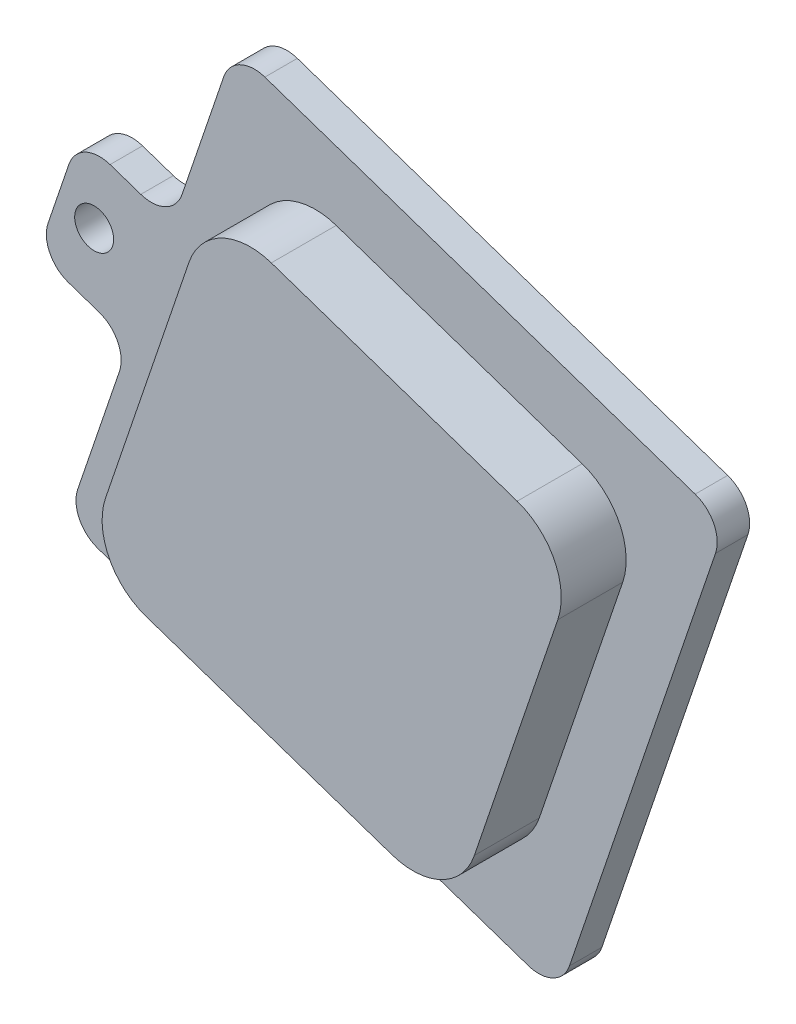
SolidWorks part; units mm, degrees
ref_plane "Front Plane" through (0, 0, 0) normal (0, 0, 1) x (1, 0, 0)
ref_plane "Top Plane" through (0, 0, 0) normal (0, 1, 0) x (1, 0, 0)
ref_plane "Right Plane" through (0, 0, 0) normal (1, 0, 0) x (0, 0, -1)
ref_plane "Plane1" through (0, 0, 3.175) normal (0, 0, 1) x (1, 0, 0)
sketch "Sketch1" plane through (0, 0, 3.175) normal (0, 0, 1) x (1, 0, 0)
  line L0 (54.9736, 15.2794) -> (-2.1524, 34.663)
  line L1 (-2.1524, 34.663) -> (-18.4755, -13.4431)
  line L2 (-18.4755, -13.4431) -> (38.6505, -32.8267)
  line L3 (38.6505, -32.8267) -> (54.9736, 15.2794)
extrude "Boss-Extrude1" add sketch "Sketch1" against normal blind 3.175
sketch "Sketch2" plane through (0, 0, 0) normal (0, 0, -1) x (-1, 0, 0)
  line L0 (2.1524, 34.663) -> (-6.8675, 31.6025)
  line L1 (-6.8675, 31.6025) -> (-0.7463, 13.5627)
  line L2 (-0.7463, 13.5627) -> (8.2736, 16.6232)
  line L3 (8.2736, 16.6232) -> (2.1524, 34.663)
extrude "Cut-Extrude1" cut sketch "Sketch2" against normal through all
sketch "Sketch3" plane through (0, 0, 0) normal (0, 0, -1) x (-1, 0, 0)
  line L0 (18.4755, -13.4431) -> (12.3544, 4.5967)
  line L1 (12.3544, 4.5967) -> (3.3345, 1.5361)
  line L2 (3.3345, 1.5361) -> (9.4556, -16.5036)
  line L3 (9.4556, -16.5036) -> (18.4755, -13.4431)
extrude "Cut-Extrude2" cut sketch "Sketch3" against normal through all
sketch "Sketch4" plane through (0, 0, 3.175) normal (0, 0, 1) x (1, 0, 0)
  line L0 (46.9199, 11.3065) -> (34.6776, -24.7731)
  line L1 (34.6776, -24.7731) -> (-1.402, -12.5308)
  line L2 (-1.402, -12.5308) -> (10.8403, 23.5488)
  line L3 (10.8403, 23.5488) -> (46.9199, 11.3065)
extrude "Boss-Extrude2" add sketch "Sketch4" along normal blind 6.35
hole_wizard "M3.5 Clearance Hole1" positions "Sketch6" profile "Sketch5" hole size "M3.5" standard "ANSI Metric"
sketch "Sketch6" plane through (0, 0, 3.175) normal (0, 0, 1) x (1, 0, 0)
  point P0 (-6.8263, 9.4266)
sketch "Sketch5" plane through (-6.8263, 9.4266, 3.175) normal (1, 0, 0) x (0, -1, 0)
  line L0 (0, 0) -> (0, 3.175)
  line L1 (0, 3.175) -> (1.905, 3.175)
  line L2 (1.905, 3.175) -> (1.905, 0)
  line L5 (1.905, 0) -> (0, 0)
  line L11 (0, -6.35) -> (0, 107.95) construction
  dimension "Thru Hole Dia." = 3.81
  dimension "Thru Hole Depth" = 3.175
fillet "Fillet1" radius 3.175 8 edges at (0.7463, 13.5627, 1.5875) (38.6505, -32.8267, 1.5875) (-9.4556, -16.5036, 1.5875) (6.8675, 31.6025, 1.5875) (54.9736, 15.2794, 1.5875) (-12.3544, 4.5967, 1.5875) (-3.3345, 1.5361, 1.5875) (-8.2736, 16.6232, 1.5875)
fillet "Fillet2" radius 6.35 4 edges at (10.8403, 23.5488, 6.35) (-1.402, -12.5308, 6.35) (34.6776, -24.7731, 6.35) (46.9199, 11.3065, 6.35)
